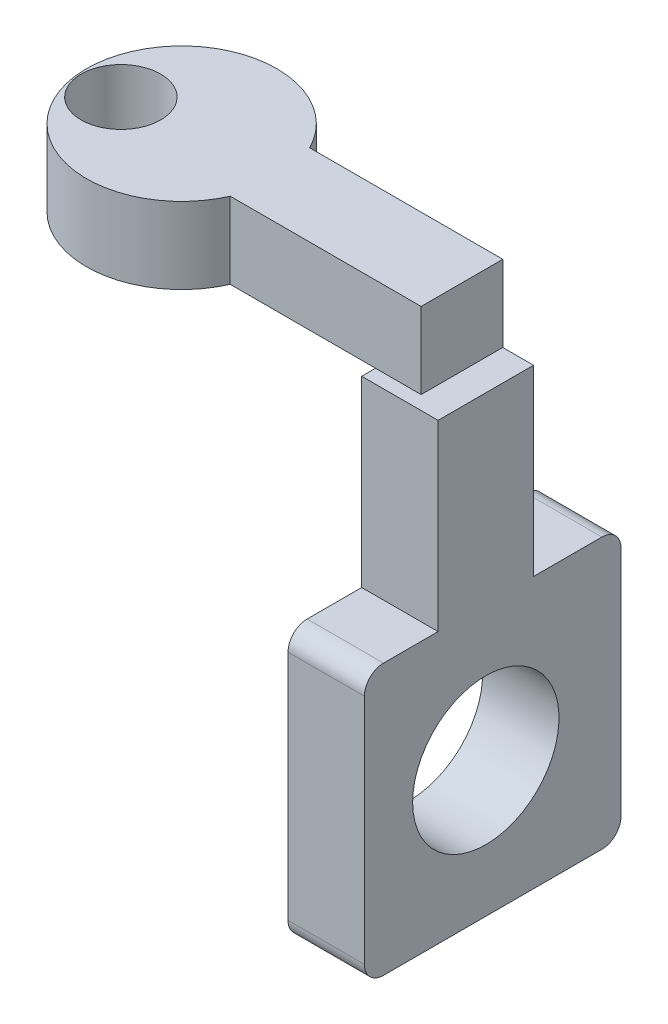
SolidWorks part; units mm, degrees
ref_plane "Ön Düzlem" through (0, 0, 0) normal (0, 0, 1) x (1, 0, 0)
ref_plane "Üst Düzlem" through (0, 0, 0) normal (0, 1, 0) x (1, 0, 0)
ref_plane "Sağ Düzlem" through (0, 0, 0) normal (1, 0, 0) x (0, 0, -1)
ref_plane "Düzlem1" through (0, 37.9375, 0) normal (0, -1, 0) x (1, 0, 0)
sketch "Çizim1" plane through (0, 37.9375, 0) normal (0, -1, 0) x (1, 0, 0)
  line L0 (-5.9865, 12.829) -> (-35.9865, 12.829)
  line L1 (-36.3277, 0) -> (-5.9865, 0)
  line L2 (-5.9865, 0) -> (-5.9865, 12.829)
  arc A0 (-35.9865, 12.829) -> (-36.3277, 0) centre (-49.6742, 6.774) ccw
  dimension "D1" = 30
extrude "Yükseklik-Ekstrüzyon1" add sketch "Çizim1" against normal blind 12
sketch "Çizim2" plane through (0, 37.9375, 0) normal (0, -1, 0) x (1, 0, 0)
  line L0 (-13.1534, 0) -> (-13.1534, 15)
  line L1 (-13.1534, 15) -> (-1.1534, 15)
  line L2 (-1.1534, 15) -> (-1.1534, 0)
  line L3 (-1.1534, 0) -> (-13.1534, 0)
extrude "Yükseklik-Ekstrüzyon2" add sketch "Çizim2" along normal blind 71.25
sketch "Çizim3" plane through (0, 0, 0) normal (0, 0, -1) x (-1, 0, 0)
  line L0 (1.1534, -33.3125) -> (1.1534, 9.1875)
  line L1 (1.1534, 9.1875) -> (13.1534, 9.1875)
  line L2 (13.1534, 9.1875) -> (13.1534, -33.3125)
  line L3 (13.1534, -33.3125) -> (1.1534, -33.3125)
extrude "Yükseklik-Ekstrüzyon3" add sketch "Çizim3" along normal blind 13.75
sketch "Çizim4" plane through (0, 0, 12.829) normal (0, 0, 1) x (1, 0, 0)
  line L0 (-13.1534, -33.3125) -> (-13.1534, 9.1875)
  line L1 (-13.1534, 9.1875) -> (-1.1534, 9.1875)
  line L2 (-1.1534, 9.1875) -> (-1.1534, -33.3125)
  line L3 (-1.1534, -33.3125) -> (-13.1534, -33.3125)
extrude "Yükseklik-Ekstrüzyon4" add sketch "Çizim4" along normal blind 13.75
hole_wizard "Ø23.0 (23) Çap Delik1" positions "Çizim6" profile "Çizim5" hole size "Ø23.0" standard "ANSI Metric"
sketch "Çizim6" plane through (-13.1534, 0, 0) normal (-1, 0, 0) x (0, 0, 1)
  point P0 (7.5, -12.0625)
sketch "Çizim5" plane through (-13.1534, -12.0625, 7.5) normal (0, 1, 0) x (0, 0, 1)
  line L0 (0, 0) -> (0, 12)
  line L1 (0, 12) -> (11.5, 12)
  line L2 (11.5, 12) -> (11.5, 0)
  line L5 (11.5, 0) -> (0, 0)
  line L11 (0, -6.35) -> (0, 107.95) construction
  dimension "Thru Hole Dia." = 23
  dimension "Thru Hole Depth" = 12
hole_wizard "Ø12.5 (12.5) Çap Delik1" positions "Çizim8" profile "Çizim7" hole size "Ø12.5" standard "ANSI Metric"
sketch "Çizim8" plane through (0, 49.9375, 0) normal (0, 1, 0) x (1, 0, 0)
  point P0 (-58.0803, -7.9203)
sketch "Çizim7" plane through (-58.0803, 49.9375, 7.9203) normal (1, 0, 0) x (0, 0, 1)
  line L0 (0, 0) -> (0, 83.25)
  line L1 (0, 83.25) -> (6.25, 83.25)
  line L2 (6.25, 83.25) -> (6.25, 0)
  line L5 (6.25, 0) -> (0, 0)
  line L11 (0, -6.35) -> (0, 107.95) construction
  dimension "Thru Hole Dia." = 12.5
  dimension "Thru Hole Depth" = 83.25
fillet "Radyus1" radius 3 4 edges at (-7.1534, 9.1875, 26.579) (-7.1534, 9.1875, -13.75) (-7.1534, -33.3125, 26.579) (-7.1534, -33.3125, -13.75)
